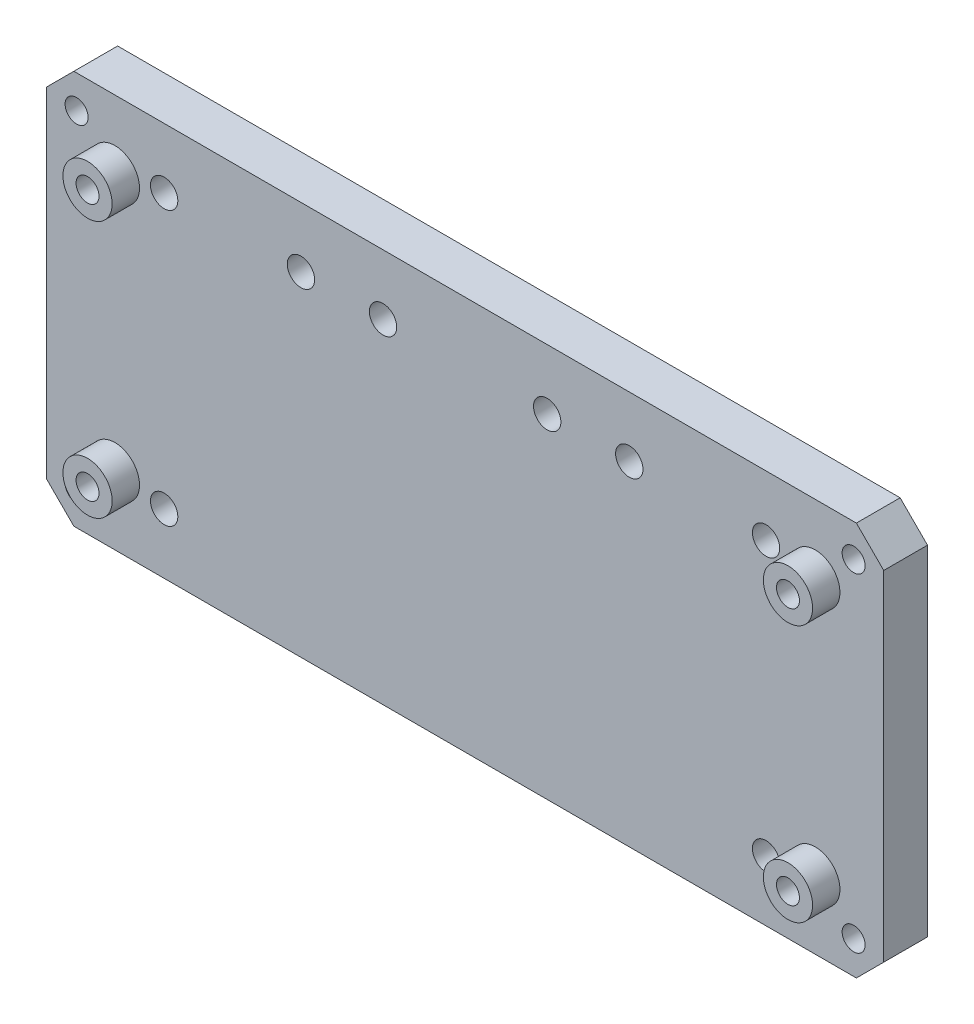
SolidWorks part; units mm, degrees
ref_plane "Front Plane" through (0, 0, 0) normal (0, 0, 1) x (1, 0, 0)
ref_plane "Top Plane" through (0, 0, 0) normal (0, 1, 0) x (1, 0, 0)
ref_plane "Right Plane" through (0, 0, 0) normal (1, 0, 0) x (0, 0, -1)
sketch "Sketch1" plane through (0, 0, 0) normal (0, 0, 1) x (1, 0, 0)
  line L0 (0, 36) -> (153, 36) construction
  line L1 (0, 0) -> (153, 0)
  line L2 (0, 0) -> (0, 72)
  line L3 (0, 72) -> (153, 72)
  line L4 (153, 0) -> (153, 72)
  line L5 (76.5, 72) -> (76.5, 0) construction
  line L6 (21.5, 61) -> (21.5, 36) construction
  line L9 (21.5, 61) -> (76.5, 61) construction
  circle A3 centre (21.5, 61) radius 2.5
  circle A4 centre (21.5, 11) radius 2.5
  circle A5 centre (131.5, 61) radius 2.5
  circle A6 centre (131.5, 11) radius 2.5
  circle A7 centre (61.5, 61) radius 2.5
  circle A8 centre (46.5, 61) radius 2.5
  circle A9 centre (106.5, 61) radius 2.5
  circle A10 centre (91.5, 61) radius 2.5
  dimension "D3" = 55
  dimension "D4" = 5
  dimension "D5" = 5
  dimension "D6" = 5
  dimension "D1" = 153
  dimension "D2" = 72
  dimension "D7" = 15
  dimension "D8" = 15
  dimension "D9" = 25
extrude "Boss-Extrude1" add sketch "Sketch1" along normal blind 8
sketch "Sketch2" plane through (0, 0, 8) normal (0, 0, 1) x (1, 0, 0)
  line L0 (76.5, 72) -> (76.5, 0) construction
  line L1 (153, 72) -> (0, 72) construction
  line L2 (0, 0) -> (153, 0) construction
  line L3 (76.5, 36) -> (12.5, 36) construction
  line L4 (12.5, 36) -> (12.5, 59.5) construction
  circle A0 centre (12.5, 59.5) radius 2.1
  circle A1 centre (12.5, 59.5) radius 4.5
  circle A2 centre (12.5, 12.5) radius 4.5
  circle A3 centre (12.5, 12.5) radius 2.1
  circle A4 centre (140.5, 59.5) radius 2.1
  circle A5 centre (140.5, 59.5) radius 4.5
  circle A6 centre (140.5, 12.5) radius 4.5
  circle A7 centre (140.5, 12.5) radius 2.1
  dimension "D2" = 4.2
  dimension "D3" = 9
  dimension "D1" = 64
  dimension "D4" = 23.5
extrude "Boss-Extrude2" add sketch "Sketch2" along normal blind 5
chamfer "Chamfer1" distance 5 angle 45 4 edges at (153, 72, 4) (153, 0, 4) (0, 72, 4) (0, 0, 4)
sketch "Sketch3" plane through (0, 0, 8) normal (0, 0, 1) x (1, 0, 0)
  line L0 (76.5, 72) -> (76.5, 0) construction
  line L1 (148, 72) -> (5, 72) construction
  line L2 (5, 0) -> (148, 0) construction
  line L3 (76.5, 36) -> (5.5, 36) construction
  line L4 (5.5, 36) -> (5.5, 6) construction
  circle A0 centre (5.5, 6) radius 2.1
  circle A1 centre (5.5, 66) radius 2.1
  circle A2 centre (147.5, 6) radius 2.1
  circle A3 centre (147.5, 66) radius 2.1
  dimension "D1" = 4.2
  dimension "D2" = 30
  dimension "D3" = 71
extrude "Cut-Extrude1" cut sketch "Sketch3" against normal blind 5
